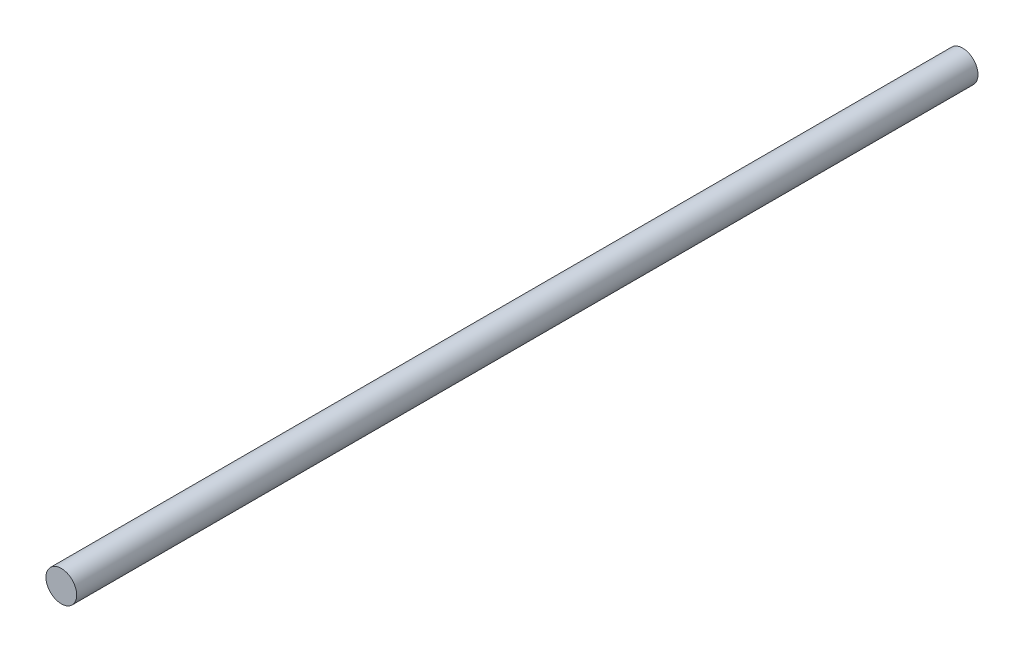
SolidWorks part; units mm, degrees
ref_plane "Front Plane" through (0, 0, 0) normal (0, 0, 1) x (1, 0, 0)
ref_plane "Top Plane" through (0, 0, 0) normal (0, 1, 0) x (1, 0, 0)
ref_plane "Right Plane" through (0, 0, 0) normal (1, 0, 0) x (0, 0, -1)
sketch "草圖1" plane through (0, 0, 0) normal (0, 0, 1) x (1, 0, 0)
  circle A0 centre (0, 0) radius 1.5
extrude "填料-伸長1" add sketch "草圖1" along normal blind 88
